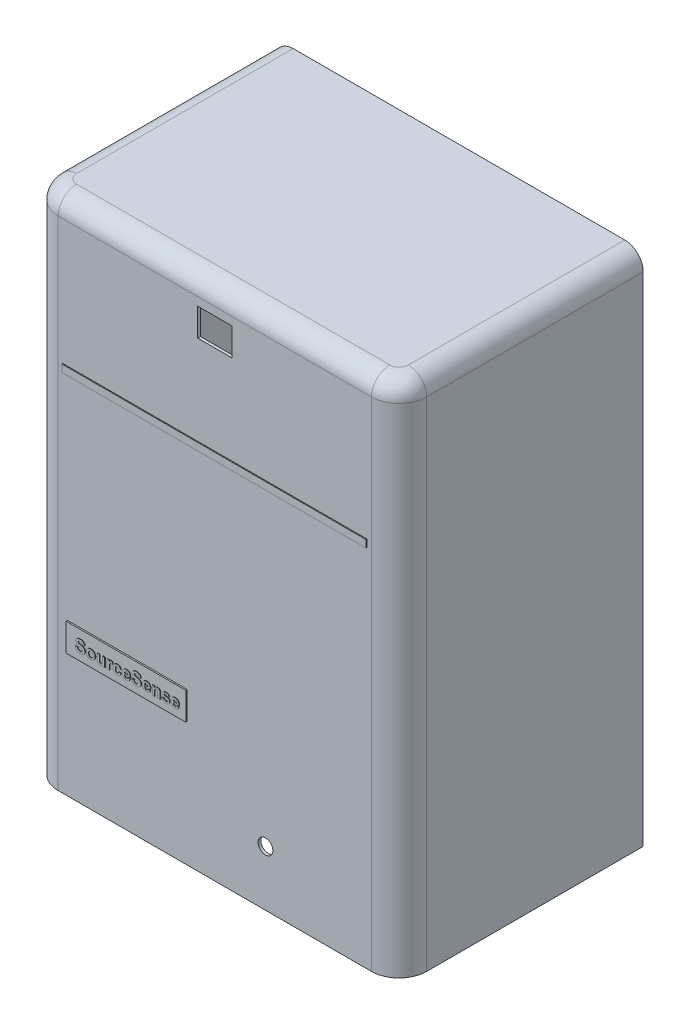
SolidWorks part; units mm, degrees
ref_plane "Front Plane" through (0, 0, 0) normal (0, 0, 1) x (1, 0, 0)
ref_plane "Top Plane" through (0, 0, 0) normal (0, 1, 0) x (1, 0, 0)
ref_plane "Right Plane" through (0, 0, 0) normal (1, 0, 0) x (0, 0, -1)
other "Configuration Table"
sketch "Sketch1" plane through (0, 0, 0) normal (0, 1, 0) x (1, 0, 0)
  line L0 (-200, -270) -> (200, -270)
  line L1 (200, -270) -> (200, -5)
  line L2 (200, -5) -> (-200, -5)
  line L3 (-200, -5) -> (-200, -270)
extrude "Cover_Block" add sketch "Sketch1" along normal blind 560
fillet "Front_Corner_R30" radius 30 2 edges at (200, 280, 270) (-200, 280, 270)
fillet "Top_Front_R20" radius 20 5 edges at (-200, 560, 122.5) (-191.2132, 560, 261.2132) (200, 560, 122.5) (191.2132, 560, 261.2132) (0, 560, 270)
shell "Shell" thickness 3
sketch "Sketch2" plane through (0, 0, 0) normal (0, 0, 1) x (1, 0, 0)
  line L0 (-18.5, 501) -> (18.5, 501)
  line L1 (18.5, 501) -> (18.5, 531)
  line L2 (18.5, 531) -> (-18.5, 531)
  line L3 (-18.5, 531) -> (-18.5, 501)
extrude "TFT_Window" cut sketch "Sketch2" against normal blind 4 from offset 270.5
sketch "Sketch3" plane through (0, 0, 0) normal (0, 0, 1) x (1, 0, 0)
  circle A0 centre (55, 60) radius 8
  dimension "D1" = 16
extrude "Tap_Hole" cut sketch "Sketch3" against normal blind 4 from offset 270.5
sketch "Sketch4" plane through (0, 0, 0) normal (0, 0, 1) x (1, 0, 0)
  line L0 (-165, 396) -> (165, 396)
  line L1 (165, 396) -> (165, 404)
  line L2 (165, 404) -> (-165, 404)
  line L3 (-165, 404) -> (-165, 396)
extrude "Accent_Strip" add sketch "Sketch4" along normal blind 1 from offset 270
sketch "Sketch5" plane through (0, 0, 0) normal (0, 0, 1) x (1, 0, 0)
  line L0 (-160, 135) -> (-30, 135)
  line L1 (-30, 135) -> (-30, 165)
  line L2 (-30, 165) -> (-160, 165)
  line L3 (-160, 165) -> (-160, 135)
extrude "Badge_Plate" add sketch "Sketch5" along normal blind 1.5 from offset 270
sketch "Sketch6" plane through (0, 0, 0) normal (0, 0, 1) x (1, 0, 0)
  text T0 "SourceSense" font "Arial" height 13
extrude "Badge_Text_SourceSense" add sketch "Sketch6" along normal blind 0.6 from offset 271.5
equation "\"Jar_OD\"= 90  'ASSUMED - Part G fallback - jar outer diameter"
equation "\"Jar_H\"= 120  'ASSUMED - Part G fallback - jar height"
equation "\"Pump_L\"= 45  'ASSUMED - Part G fallback"
equation "\"Pump_W\"= 24  'ASSUMED - Part G fallback"
equation "\"Pump_H\"= 33  'ASSUMED - Part G fallback"
equation "\"Pump_Outlet_OD\"= 7.5  'ASSUMED - Part G fallback"
equation "\"Tube_OD\"= 8  'ASSUMED - Part G fallback"
equation "\"Tube_ID\"= 6  'ASSUMED - Part G fallback"
equation "\"TDS_Body_Dia\"= 12  'ASSUMED - Part G fallback"
equation "\"TDS_Wet_Len\"= 45  'ASSUMED - Part G fallback - length in water"
equation "\"DS_Tube_Dia\"= 6  'ASSUMED - Part G fallback"
equation "\"DS_Tube_Len\"= 50  'ASSUMED - Part G fallback"
equation "\"ORP_Body_Dia\"= 12  'ASSUMED - Part G fallback"
equation "\"ORP_Body_Len\"= 150  'ASSUMED - Part G fallback"
equation "\"ORP_Cap_Dia\"= 16  'ASSUMED - Part G fallback"
equation "\"Turb_W\"= 33  'ASSUMED - Part G fallback - head width"
equation "\"Turb_D\"= 28  'ASSUMED - Part G fallback - head depth"
equation "\"Turb_H\"= 30  'ASSUMED - Part G fallback - head height"
equation "\"Turb_Slot_W\"= 10  'ASSUMED - Part G fallback - slot width"
equation "\"Flow_L\"= 62  'ASSUMED - Part G fallback YF-S201"
equation "\"Flow_W\"= 36  'ASSUMED - Part G fallback"
equation "\"Flow_H\"= 35  'ASSUMED - Part G fallback"
equation "\"Thread_G12_OD\"= 20.955  'ASSUMED - Part G fallback thread G1/2 (major diameter)"
equation "\"Valve_L\"= 75  'ASSUMED - Part G fallback"
equation "\"Valve_W\"= 45  'ASSUMED - Part G fallback"
equation "\"Valve_H\"= 60  'ASSUMED - Part G fallback"
equation "\"Tee_L\"= 40  'ASSUMED - Part G fallback - overall length"
equation "\"Tee_Branch_L\"= 25  'ASSUMED - Part G fallback"
equation "\"Tee_OD\"= 12  'ASSUMED - Part G fallback"
equation "\"LED_Board_L\"= 20  'ASSUMED - Part G fallback"
equation "\"LED_Board_W\"= 20  'ASSUMED - Part G fallback - LED at centre"
equation "\"GUVA_L\"= 20  'ASSUMED - Part G fallback"
equation "\"GUVA_W\"= 12  'ASSUMED - Part G fallback - sensor at centre"
equation "\"Reed_L\"= 27  'ASSUMED - Part G fallback MC-38 half"
equation "\"Reed_W\"= 14  'ASSUMED - Part G fallback"
equation "\"Reed_H\"= 8  'ASSUMED - Part G fallback"
equation "\"ESP_L\"= 51  'ASSUMED - Part G fallback"
equation "\"ESP_W\"= 28  'ASSUMED - Part G fallback"
equation "\"TFT_L\"= 58  'ASSUMED - Part G fallback - board"
equation "\"TFT_W\"= 35  'ASSUMED - Part G fallback - board"
equation "\"TFT_Win_L\"= 35  'ASSUMED - Part G fallback - visible window"
equation "\"TFT_Win_W\"= 28  'ASSUMED - Part G fallback - visible window"
equation "\"Relay_L\"= 50  'ASSUMED - Part G fallback"
equation "\"Relay_W\"= 26  'ASSUMED - Part G fallback"
equation "\"Relay_H\"= 19  'ASSUMED - Part G fallback"
equation "\"Mosfet_L\"= 34  'ASSUMED - Part G fallback"
equation "\"Mosfet_W\"= 17  'ASSUMED - Part G fallback"
equation "\"Mosfet_H\"= 12  'ASSUMED - Part G fallback"
equation "\"TDS_Board_L\"= 42  'ASSUMED - Part G fallback"
equation "\"TDS_Board_W\"= 32  'ASSUMED - Part G fallback"
equation "\"Turb_Board_L\"= 38  'ASSUMED - Part G fallback"
equation "\"Turb_Board_W\"= 28  'ASSUMED - Part G fallback"
equation "\"BNC_Thread_Dia\"= 9.5  'ASSUMED - Part G fallback"
equation "\"Plate_L\"= 420  'ASSUMED - Part G fallback"
equation "\"Plate_W\"= 297  'ASSUMED - Part G fallback"
equation "\"Plate_T\"= 6  'ASSUMED - Part G fallback"
equation "\"Booster_L\"= 150  'ASSUMED - Part G fallback - booster pump"
equation "\"Booster_W\"= 95  'ASSUMED - Part G fallback"
equation "\"Booster_H\"= 100  'ASSUMED - Part G fallback"
equation "\"PTube_OD\"= 6.35  'ASSUMED - Part G fallback - product tube 1/4 inch"
equation "\"Qz_Out\"= 12  'ASSUMED - Part G fallback - quartz channel outside square"
equation "\"Qz_Path\"= 10  'ASSUMED - Part G fallback - quartz channel inside light path"
equation "\"Qz_L\"= 40  'ASSUMED - Part G fallback - quartz channel length"
equation "\"LED860_Dia\"= 5  'ASSUMED - Part G fallback - 860 nm LED"
equation "\"BPW_L\"= 5.4  'ASSUMED - Part G fallback - BPW34"
equation "\"BPW_W\"= 4.3  'ASSUMED - Part G fallback - BPW34"
equation "\"Cart_Dia\"= 50  'ASSUMED - Part G fallback - sediment and pre-carbon cartridges"
equation "\"Cart_L\"= 255  'ASSUMED - Part G fallback"
equation "\"UF_Dia\"= 50  'ASSUMED - Part G fallback - UF cartridge"
equation "\"UF_L\"= 260  'ASSUMED - Part G fallback"
equation "\"RO_Dia\"= 62  'ASSUMED - Part G fallback - RO membrane housing"
equation "\"RO_L\"= 300  'ASSUMED - Part G fallback"
equation "\"UVC_Dia\"= 40  'ASSUMED - Part G fallback - UV-C chamber"
equation "\"UVC_L\"= 300  'ASSUMED - Part G fallback"
equation "\"Tank_W\"= 260  'ASSUMED - Part G fallback - storage tank"
equation "\"Tank_D\"= 160  'ASSUMED - Part G fallback"
equation "\"Tank_H\"= 300  'ASSUMED - Part G fallback"
equation "\"Cab_W\"= 400  'ASSUMED - Part G fallback - purifier cabinet"
equation "\"Cab_D\"= 270  'ASSUMED - Part G fallback"
equation "\"Cab_H\"= 560  'ASSUMED - Part G fallback"
equation "\"ORP_Board_L\"= 40  'ASSUMED - Part G fallback - ORP buffer board"
equation "\"ORP_Board_W\"= 30  'ASSUMED - Part G fallback"
equation "\"Opt_Board_L\"= 50  'ASSUMED - Part G fallback - optical front-end board"
equation "\"Opt_Board_W\"= 40  'ASSUMED - Part G fallback"
equation "\"Buck_L\"= 43  'ASSUMED - Part G fallback - 12 V to 5 V buck module"
equation "\"Buck_W\"= 21  'ASSUMED - Part G fallback"
equation "\"Buck_H\"= 14  'ASSUMED - Part G fallback"
equation "\"BB_L\"= 165  'ASSUMED - Part G fallback - breadboard (As_Built_R3 only)"
equation "\"BB_W\"= 55  'ASSUMED - Part G fallback"
equation "\"BB_H\"= 10  'ASSUMED - Part G fallback"
equation "\"Cuv_W\"= 12.5  'ASSUMED - old R3 cuvette (station suppressed in SS4)"
equation "\"Cuv_D\"= 12.5  'ASSUMED - old R3 cuvette (station suppressed in SS4)"
equation "\"Cuv_H\"= 45  'ASSUMED - old R3 cuvette (station suppressed in SS4)"
equation "\"Probe_Clr\"= 0.3  'DESIGN VALUE - Part C rule 3 - printed probe hole = diameter + 0.3"
equation "\"Label_H\"= 0.6  'DESIGN VALUE - Part D - raised label height"
equation "\"D1@Badge_Text_SourceSense\" = \"Label_H\""
